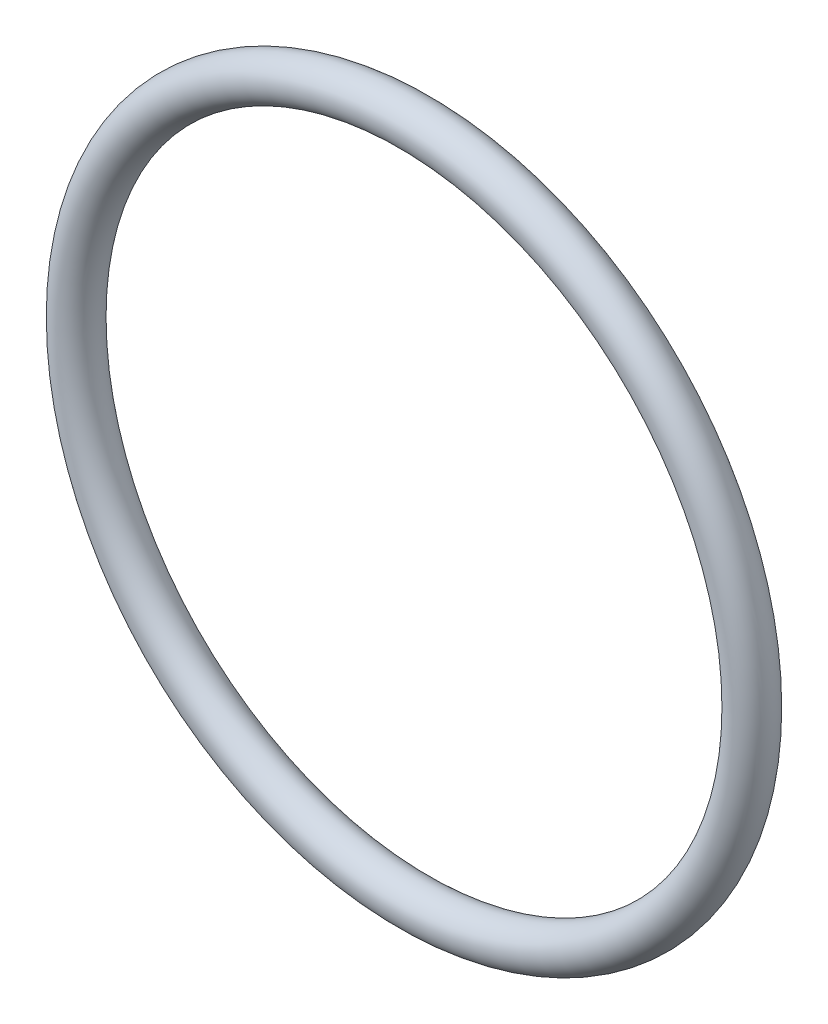
SolidWorks part; units mm, degrees
ref_plane "Front Plane" through (0, 0, 0) normal (0, 0, 1) x (1, 0, 0)
ref_plane "Top Plane" through (0, 0, 0) normal (0, 1, 0) x (1, 0, 0)
ref_plane "Right Plane" through (0, 0, 0) normal (1, 0, 0) x (0, 0, -1)
sketch "Sketch1" plane through (0, 0, 0) normal (0, 0, 1) x (1, 0, 0)
  line L0 (-63.5, 0) -> (63.5, 0) construction
  line L1 (0, 0) -> (14.2925, -14.2925) construction
  circle A0 centre (0, 0) radius 20.2127 construction
  point P3 (0, 20.2127)
  point P6 (0, 0)
  point P9 (14.2925, -14.2925)
  dimension "D1" = 40.4254
  dimension "Outer Circumference" = 127
  dimension "D2" = 45
sketch "Sketch2" plane through (0, 0, 0) normal (1, 0, 0) x (0, 0, -1)
  line L0 (0, 20.2127) -> (0, -20.2127) construction
  circle A0 centre (0, 19.0221) radius 1.1906 construction
  dimension "Diameter" = 2.3813
sketch "Sketch3" plane through (0, 0, 0) normal (0, 0, 1) x (1, 0, 0)
  circle A0 centre (0, 0) radius 20.2127
  circle A1 centre (0, 0) radius 20.2127 construction
  circle A2 centre (0, 0) radius 19.0221
sketch "Sketch4" plane through (0, 0, 0) normal (1, 0, 0) x (0, 0, -1)
  circle A0 centre (0, 19.0221) radius 1.1906 construction
  circle A1 centre (0, 19.0221) radius 1.1906
sweep "Sweep2" add profiles "Sketch4" path "Sketch3"
equation "\"D1@Sketch1\"=(\"Outer Circumference@Sketch1\"/(2*pi))*2"
